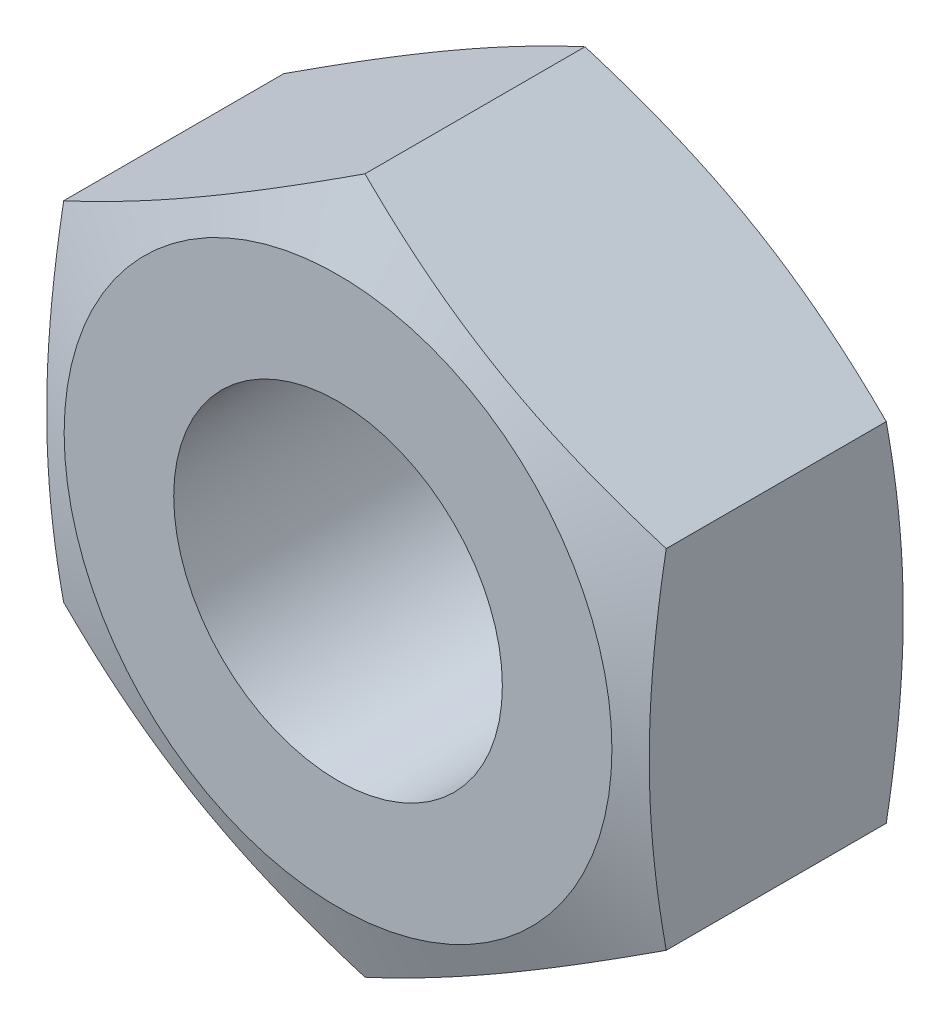
SolidWorks part; units mm, degrees
material "AISI 304"
ref_plane "Front Plane" through (0, 0, 0) normal (0, 0, 1) x (1, 0, 0)
ref_plane "Top Plane" through (0, 0, 0) normal (0, 1, 0) x (1, 0, 0)
ref_plane "Right Plane" through (0, 0, 0) normal (1, 0, 0) x (0, 0, -1)
sketch "Sketch1" plane through (0, 0, 0) normal (0, 0, 1) x (1, 0, 0)
  line L1 (0, 3.1754) -> (-2.75, 1.5877)
  line L2 (-2.75, 1.5877) -> (-2.75, -1.5877)
  line L3 (-2.75, -1.5877) -> (0, -3.1754)
  line L4 (0, -3.1754) -> (2.75, -1.5877)
  line L5 (2.75, -1.5877) -> (2.75, 1.5877)
  line L6 (2.75, 1.5877) -> (0, 3.1754)
  circle A0 centre (0, 0) radius 1.5
  circle A1 centre (0, 0) radius 2.75 construction
  point P3 (0, 0)
  dimension "D1" = 5.5
  dimension "D2" = 3
extrude "Boss-Extrude1" add sketch "Sketch1" along normal mid plane 2.5
sketch "Sketch2" plane through (0, 0, 1.25) normal (0, 0, 1) x (1, 0, 0)
  circle A0 centre (0, 0) radius 2.5
  dimension "D1" = 5
extrude "Cut-Extrude1" cut sketch "Sketch2" against normal blind 2.5 draft 70 flip side to cut
mirror "Mirror1" about plane through (0, 0, 0) normal (0, 0, 1) of "Cut-Extrude1"
